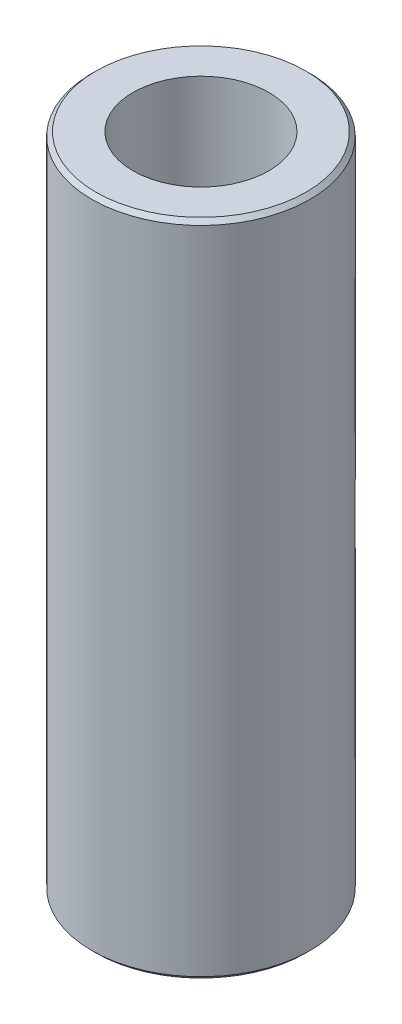
SolidWorks part; units mm, degrees
ref_plane "Ön Düzlem" through (0, 0, 0) normal (0, 0, 1) x (1, 0, 0)
ref_plane "Üst Düzlem" through (0, 0, 0) normal (0, 1, 0) x (1, 0, 0)
ref_plane "Sağ Düzlem" through (0, 0, 0) normal (1, 0, 0) x (0, 0, -1)
sketch "Çizim1" plane through (0, 0, 0) normal (0, 1, 0) x (1, 0, 0)
  circle A0 centre (0, 0) radius 2.65
  circle A1 centre (0, 0) radius 1.65
  dimension "D1" = 3.3
  dimension "D2" = 5.3
extrude "Yükseklik-Ekstrüzyon1" add sketch "Çizim1" along normal blind 16
chamfer "Pah1" distance 0.1 angle 45 2 edges at (0, 0, 2.65) (0, 16, 2.65)
sketch "Çizim2" plane through (0, 0, 0) normal (1, 0, 0) x (0, 0, -1)
  line L0 (-2.65, 8) -> (2.65, 8) construction
  line L1 (-2.65, 15.9) -> (-2.65, 0.1) construction
  line L2 (2.65, 0.1) -> (2.65, 15.9) construction
  line L3 (2.65, 9.9209) -> (2.65, 6.0791) construction
  line L4 (2.65, 0.1) -> (2.65, 15.9) construction
  circle A0 centre (4.25, 8) radius 2.5
  point P10 (3.189, 10.3079)
  dimension "D1" = 5
  dimension "D2" = 1.6
extrude "Kes-Ekstrüzyon1" cut sketch "Çizim2" against normal mid plane 17.6
